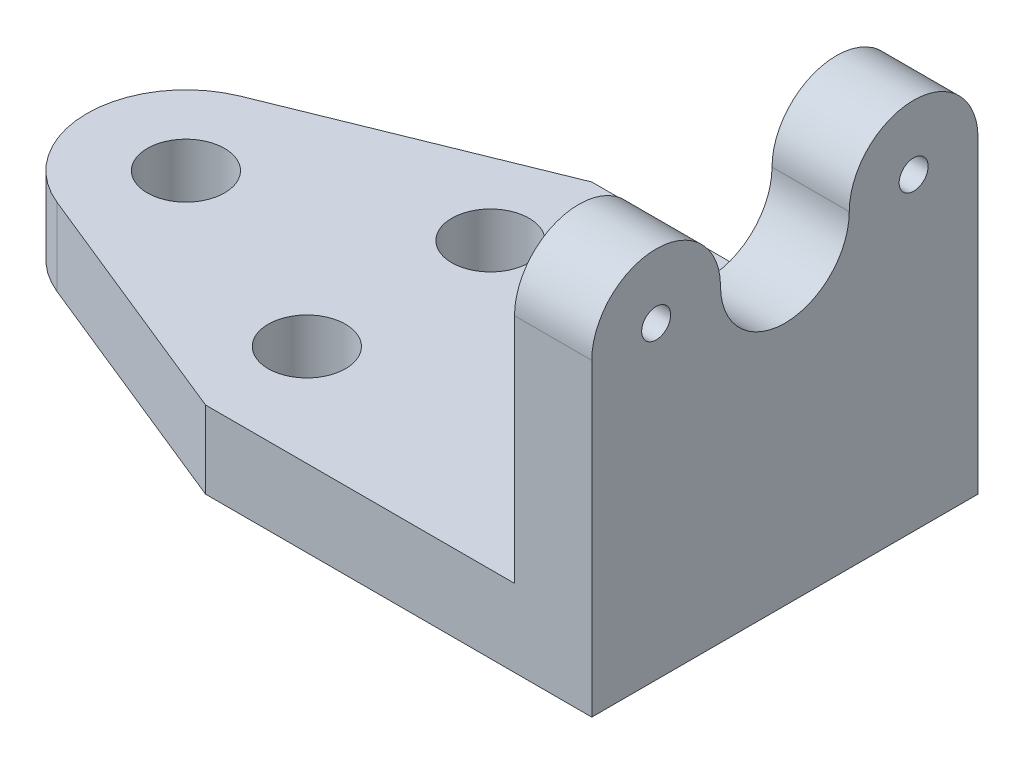
SolidWorks part; units mm, degrees
ref_plane "前视基准面" through (0, 0, 0) normal (0, 0, 1) x (1, 0, 0)
ref_plane "上视基准面" through (0, 0, 0) normal (0, 1, 0) x (1, 0, 0)
ref_plane "右视基准面" through (0, 0, 0) normal (1, 0, 0) x (0, 0, -1)
other "Configuration Table"
sketch "草图2" plane through (0, 0, 0) normal (0, 1, 0) x (1, 0, 0)
  line L0 (-20, 20) -> (-45.8833, 9.5053)
  line L1 (-20, 20) -> (20, 20)
  line L2 (-20, 20) -> (-20, -20) construction
  line L3 (-20, -20) -> (20, -20)
  line L4 (20, 20) -> (20, -20)
  line L5 (0, -20) -> (0, 20) construction
  line L6 (-20, 0) -> (20, 0) construction
  line L7 (-45.8833, -9.5053) -> (-20, -20)
  arc A0 (-45.8833, 9.5053) -> (-45.8833, -9.5053) centre (-42.0293, 0) ccw
  circle A1 centre (-42.0293, 0) radius 4
  circle A2 centre (-20, 9.5053) radius 4
  circle A3 centre (-20, -9.5053) radius 4
  point P0 (0, 0)
  dimension "D3" = 8
  dimension "D1" = 40
  dimension "D2" = 40
extrude "凸台-拉伸1" add sketch "草图2" along normal blind 8
sketch "草图3" plane through (20, 0, 0) normal (1, 0, 0) x (0, 0, -1)
  line L1 (-20, 0) -> (20, 0)
  line L2 (-20, 0) -> (-20, 32)
  line L4 (20, 0) -> (20, 32)
  arc A0 (-20, 32) -> (-6.6667, 32) centre (-13.3333, 32) cw
  arc A1 (-6.6667, 32) -> (6.6667, 32) centre (0, 32) ccw
  arc A2 (6.6667, 32) -> (20, 32) centre (13.3333, 32) cw
  circle A3 centre (-13.3333, 32) radius 1.5
  circle A4 centre (13.3333, 32) radius 1.5
  dimension "D3" = 3
  dimension "D1" = 32
  dimension "D2" = 40
extrude "凸台-拉伸4" add sketch "草图3" against normal blind 8
ref_plane "基准面1" through (0, 0, -4) normal (0, 0, 1) x (1, 0, 0)
sketch "草图9" plane through (0, 0, 0) normal (0, 0, 1) x (1, 0, 0)
  line L0 (-2, 8) -> (12, 22)
  line L1 (-20, 8) -> (12, 8) construction
  line L2 (12, 32) -> (12, 8) construction
  point P8 (0.2783, 4.1964)
  dimension "D1" = 14
  dimension "D2" = 14
rib "筋1" sketch "草图9" sketch "草图9" thickness 8 extrusion direction parallel to sketch draft on no parameters "D1"=8
